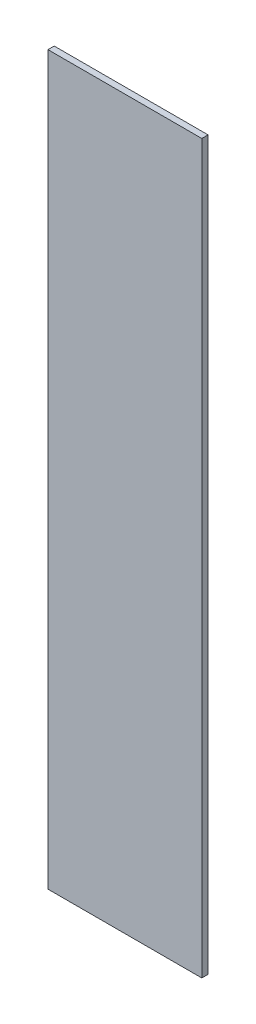
SolidWorks part; units mm, degrees
ref_plane "Front Plane" through (0, 0, 0) normal (0, 0, 1) x (1, 0, 0)
ref_plane "Top Plane" through (0, 0, 0) normal (0, 1, 0) x (1, 0, 0)
ref_plane "Right Plane" through (0, 0, 0) normal (1, 0, 0) x (0, 0, -1)
sketch "Croquis1" plane through (0, 0, 0) normal (0, 0, 1) x (1, 0, 0)
  line L1 (-38.1, 180) -> (38.1, 180)
  line L2 (-38.1, 180) -> (-38.1, -180)
  line L3 (-38.1, -180) -> (38.1, -180)
  line L4 (38.1, 180) -> (38.1, -180)
  line L5 (-38.1, 180) -> (38.1, -180) construction
  line L6 (-38.1, -180) -> (38.1, 180) construction
  point P0 (0, 0)
  dimension "D1" = 360
  dimension "D2" = 76.2
extrude "Saliente-Extruir1" add sketch "Croquis1" along normal blind 3.1
